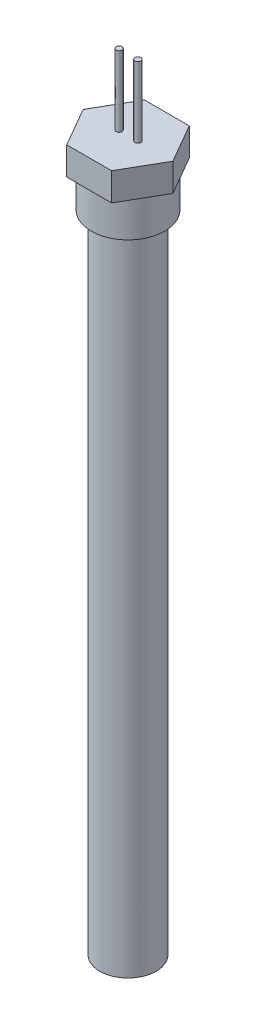
SolidWorks part; units mm, degrees
ref_plane "Front Plane" through (0, 0, 0) normal (0, 0, 1) x (1, 0, 0)
ref_plane "Top Plane" through (0, 0, 0) normal (0, 1, 0) x (1, 0, 0)
ref_plane "Right Plane" through (0, 0, 0) normal (1, 0, 0) x (0, 0, -1)
sketch "Sketch1" plane through (0, 0, 0) normal (0, 1, 0) x (1, 0, 0)
  circle A0 centre (0, 0) radius 8
  dimension "D1" = 16
extrude "Boss-Extrude1" add sketch "Sketch1" along normal blind 201
sketch "Sketch2" plane through (0, 201, 0) normal (0, 1, 0) x (1, 0, 0)
  circle A0 centre (-2.575, 0.0667) radius 0.8284
  circle A1 centre (2.75, 0.0667) radius 0.8427
extrude "Boss-Extrude2" add sketch "Sketch2" along normal blind 20
sketch "Sketch3" plane through (0, 201, 0) normal (0, 1, 0) x (1, 0, 0)
  line L1 (12.7017, 0) -> (6.3509, 11)
  line L2 (6.3509, 11) -> (-6.3509, 11)
  line L3 (-6.3509, 11) -> (-12.7017, 0)
  line L4 (-12.7017, 0) -> (-6.3509, -11)
  line L5 (-6.3509, -11) -> (6.3509, -11)
  line L6 (6.3509, -11) -> (12.7017, 0)
  circle A0 centre (0, 0) radius 11 construction
  dimension "D1" = 22
extrude "Boss-Extrude3" add sketch "Sketch3" against normal blind 7.9
sketch "Sketch4" plane through (0, 193.1, 0) normal (0, -1, 0) x (1, 0, 0)
  circle A0 centre (0, 0) radius 10.4
  circle A1 centre (0, 0) radius 8 construction
  circle A2 centre (0, 0) radius 8
  dimension "D1" = 20.8
extrude "Boss-Extrude4" add sketch "Sketch4" along normal blind 10.4
